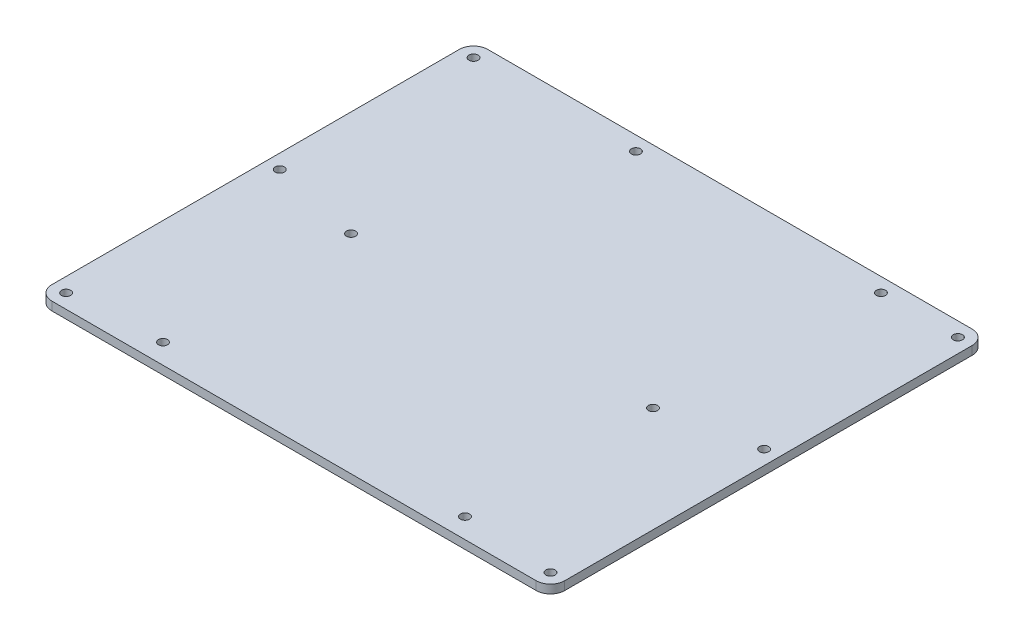
SolidWorks part; units mm, degrees
ref_plane "前视基准面" through (0, 0, 0) normal (0, 0, 1) x (1, 0, 0)
ref_plane "上视基准面" through (0, 0, 0) normal (0, 1, 0) x (1, 0, 0)
ref_plane "右视基准面" through (0, 0, 0) normal (1, 0, 0) x (0, 0, -1)
other "Configuration Table"
sketch "草图1" plane through (0, 0, 0) normal (0, 1, 0) x (1, 0, 0)
  line L1 (-85, 76.5) -> (85, 76.5)
  line L2 (-90, 71.5) -> (-90, -71.5)
  line L3 (-85, -76.5) -> (85, -76.5)
  line L4 (90, 71.5) -> (90, -71.5)
  line L5 (-90, 76.5) -> (90, -76.5) construction
  line L6 (-90, -76.5) -> (90, 76.5) construction
  arc A0 (-90, -71.5) -> (-85, -76.5) centre (-85, -71.5) ccw
  arc A1 (85, -76.5) -> (90, -71.5) centre (85, -71.5) ccw
  arc A2 (85, 76.5) -> (90, 71.5) centre (85, 71.5) cw
  arc A3 (-85, 76.5) -> (-90, 71.5) centre (-85, 71.5) ccw
  point P0 (0, 0)
  dimension "D3" = 5
  dimension "D1" = 180
  dimension "D2" = 153
extrude "凸台-拉伸1" add sketch "草图1" along normal blind 3
sketch "草图2" plane through (0, 3, 0) normal (0, 1, 0) x (1, 0, 0)
  circle A0 centre (-85, 71.5) radius 1.6
  circle A1 centre (85, 71.5) radius 1.6
  circle A2 centre (85, -71.5) radius 1.6
  circle A3 centre (-85, -71.5) radius 1.6
  circle A4 centre (-53, -69.5) radius 1.6
  circle A5 centre (53, -69.5) radius 1.6
  circle A6 centre (53, -3.5) radius 1.6
  circle A7 centre (-53, -3.5) radius 1.6
  circle A8 centre (-28, 71.5) radius 1.6
  circle A9 centre (58, 71.5) radius 1.6
  circle A10 centre (-85, 3.5) radius 1.6
  circle A11 centre (85, 3.5) radius 1.6
  dimension "D1" = 3.2
  dimension "D3" = 86
  dimension "D5" = 2
  dimension "D9" = 7
  dimension "D11" = 7
  dimension "D2" = 57
  dimension "D4" = 32
  dimension "D6" = 106
  dimension "D7" = 66
  dimension "D8" = 32
  dimension "D10" = 32
extrude "切除-拉伸1" cut sketch "草图2" against normal up to next
